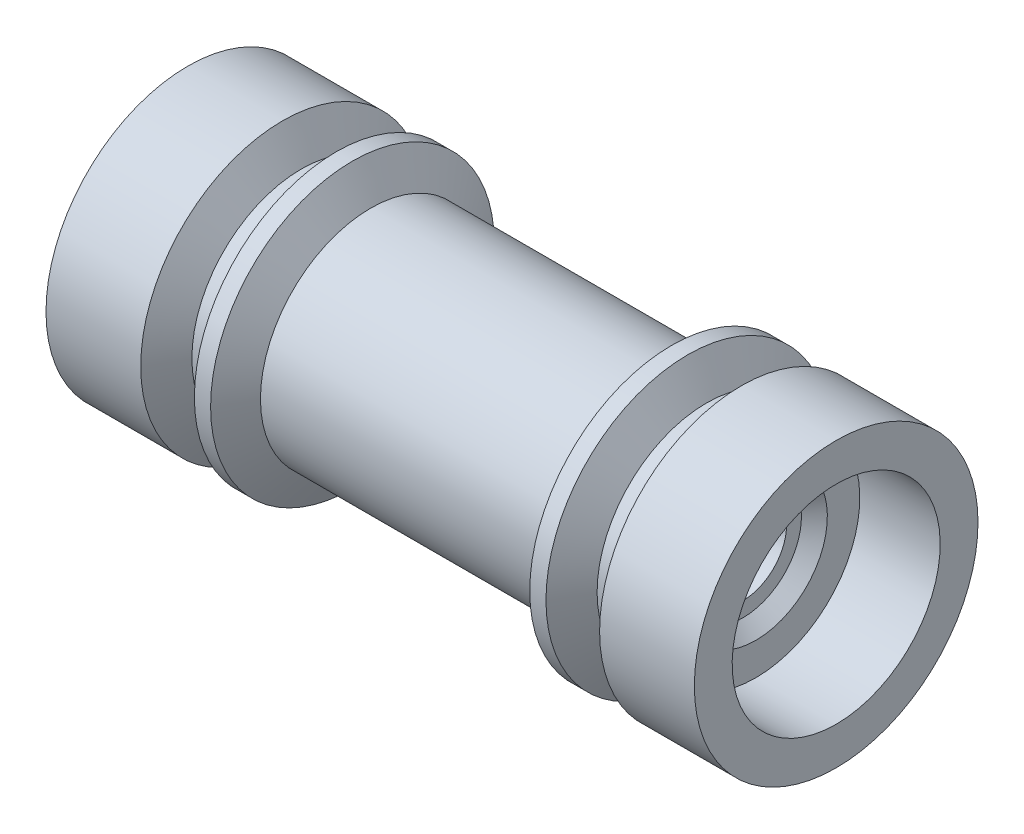
SolidWorks part; units mm, degrees
ref_plane "Front Plane" through (0, 0, 0) normal (0, 0, 1) x (1, 0, 0)
ref_plane "Top Plane" through (0, 0, 0) normal (0, 1, 0) x (1, 0, 0)
ref_plane "Right Plane" through (0, 0, 0) normal (1, 0, 0) x (0, 0, -1)
sketch "Sketch2" plane through (0, 0, 0) normal (0, 0, 1) x (1, 0, 0)
  line L0 (0, 0) -> (0, 28.4375) construction
  line L1 (-12.7, 4.075) -> (-9.55, 4.075) construction
  line L2 (-12.7, 4.075) -> (-12.7, -4.075) construction
  line L3 (-12.7, -4.075) -> (-9.55, -4.075) construction
  line L4 (-9.55, 4.075) -> (-9.55, -4.075) construction
  line L5 (-12.7, 4.075) -> (-9.55, -4.075) construction
  line L6 (-12.7, -4.075) -> (-9.55, 4.075) construction
  line L7 (9.55, 4.5) -> (54.0332, 4.5) construction
  line L8 (9.55, 4.5) -> (9.55, -4.5) construction
  line L9 (9.55, -4.5) -> (54.0332, -4.5) construction
  line L10 (54.0332, 4.5) -> (54.0332, -4.5) construction
  line L11 (9.55, 4.5) -> (54.0332, -4.5) construction
  line L12 (9.55, -4.5) -> (54.0332, 4.5) construction
  line L13 (-12.7, 0) -> (54.0332, 0) construction
  line L14 (-12.7, 5.5562) -> (-8.9882, 5.5562)
  line L21 (-5.5369, 4.318) -> (0, 4.318)
  line L22 (-12.7, 5.5562) -> (-12.7, 4.075)
  line L23 (-12.7, 4.075) -> (-9.55, 4.075)
  line L24 (-9.55, 4.075) -> (-9.55, 0)
  line L25 (-9.55, 0) -> (0, 0)
  line L26 (0, 0) -> (0, 4.318)
  line L27 (-33.5594, -5.5562) -> (-33.5594, 5.5562) construction
  line L28 (-8.9882, 5.5562) -> (-8.255, 4.2862)
  line L29 (-8.255, 4.2862) -> (-7.62, 4.2862)
  line L30 (-12.7, 5.5562) -> (12.7, 5.5562) construction
  line L31 (0, 1.6) -> (-12.5, 1.6)
  line L32 (-12.5, 1.6) -> (-14.1, 0)
  line L33 (-12.5, 1.6) -> (-12.5, -1.6) construction
  line L34 (-12.5, 1.6) -> (12.5, 1.6) construction
  line L35 (-9.55, 1.7145) -> (-2.875, 1.7145)
  line L36 (-2.875, 1.7145) -> (-2.875, 0)
  line L37 (-9.55, 2.805) -> (-9.042, 2.297)
  line L38 (-2.875, 1.7145) -> (-15.875, 1.7145) construction
  line L39 (-2.875, 1.7145) -> (-2.875, -1.7145) construction
  line L40 (-2.875, -1.7145) -> (-15.875, -1.7145) construction
  line L41 (-15.875, 1.7145) -> (-15.875, -1.7145) construction
  line L42 (-9.042, 2.297) -> (-9.042, 0)
  line L46 (-7.62, 4.2862) -> (-6.8868, 5.5562)
  line L47 (-6.8868, 5.5562) -> (-6.2518, 5.5562)
  line L48 (-6.2518, 5.5562) -> (-5.5369, 4.318)
  line L49 (-7.9375, 4.2862) -> (-7.9375, 6.3987) construction
  line L50 (-7.9375, 6.3987) -> (7.9375, 6.3987) construction
  point P0 (-11.125, 0)
  point P5 (31.7916, 0)
  point P27 (-33.5594, 0)
  point P29 (-12.5, 0)
  point P33 (0, 6.3987)
  point P36 (0, 1.6)
  point P48 (-2.875, 0)
  point P51 (0, 5.5562)
  dimension "D3" = 4.318
  dimension "D4" = 11.1125
  dimension "D5" = 8.15
  dimension "D6" = 60
  dimension "D7" = 0.635
  dimension "D8" = 60
  dimension "D9" = 15.875
  dimension "D10" = 1.27
  dimension "D11" = 25.4
  dimension "D12" = 0.635
  dimension "D13" = 45
  dimension "D14" = 25
  dimension "D15" = 3.2
  dimension "D16" = 3.429
  dimension "D17" = 3.175
  dimension "D18" = 1.27
  dimension "D19" = 0.508
  dimension "D20" = 45
  dimension "D21" = 13
  dimension "D22" = 3.15
revolve "Revolve1" add sketch "Sketch2" angle 360 about L13
mirror "Mirror1" about plane through (0, 0, 0) normal (1, 0, 0) of bodies 101
chamfer "Chamfer1" distance 0.508 angle 45 1 edges at (-12.7, -4.075, 0)
